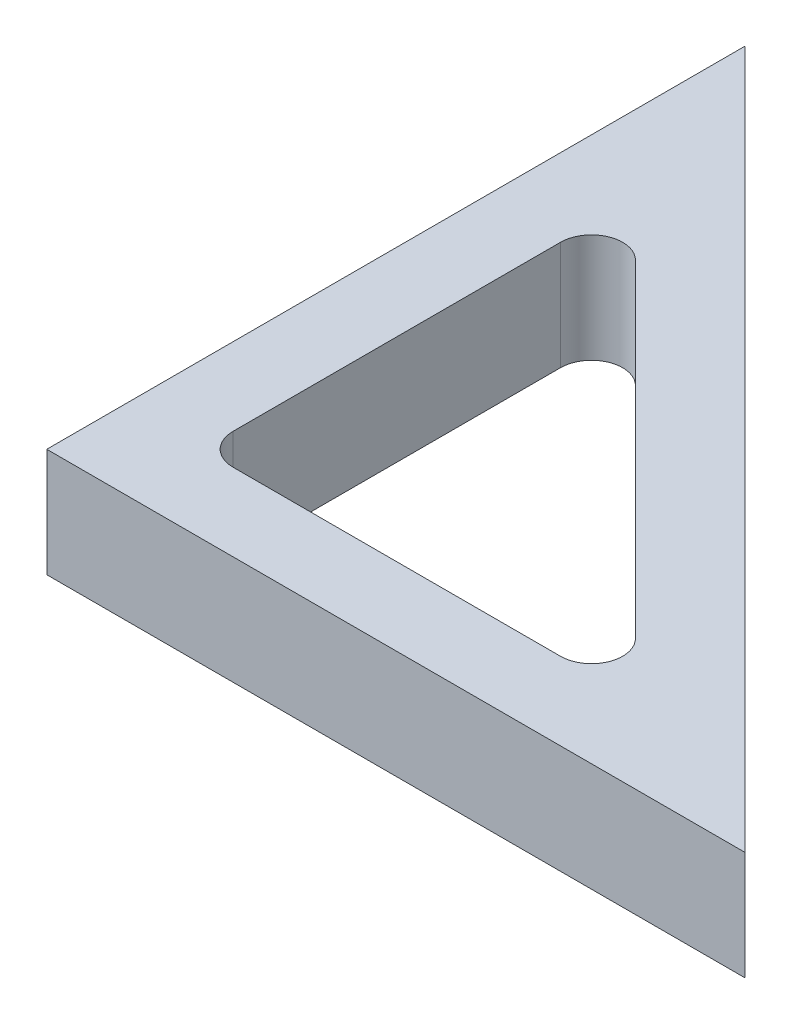
SolidWorks part; units mm, degrees
ref_plane "Front Plane" through (0, 0, 0) normal (0, 0, 1) x (1, 0, 0)
ref_plane "Top Plane" through (0, 0, 0) normal (0, 1, 0) x (1, 0, 0)
ref_plane "Right Plane" through (0, 0, 0) normal (1, 0, 0) x (0, 0, -1)
sketch "Sketch1" plane through (0, 0, 0) normal (0, 1, 0) x (1, 0, 0)
  line L0 (0, 0) -> (0, 45)
  line L1 (0, 0) -> (45, 0)
  line L2 (0, 45) -> (45, 0)
  line L3 (5, 7) -> (5, 28.1005)
  line L4 (8.4142, 29.5147) -> (29.5147, 8.4142)
  line L5 (7, 5) -> (28.1005, 5)
  line L6 (5, 32.9289) -> (32.9289, 5) construction
  line L7 (5, 5) -> (32.9289, 5) construction
  line L8 (5, 5) -> (5, 32.9289) construction
  arc A0 (29.5147, 8.4142) -> (28.1005, 5) centre (28.1005, 7) cw
  arc A1 (5, 7) -> (7, 5) centre (7, 7) ccw
  arc A2 (8.4142, 29.5147) -> (5, 28.1005) centre (7, 28.1005) ccw
  dimension "D4" = 2
  dimension "D1" = 45
  dimension "D2" = 45
  dimension "D3" = 5
extrude "Boss-Extrude1" add sketch "Sketch1" along normal blind 7
